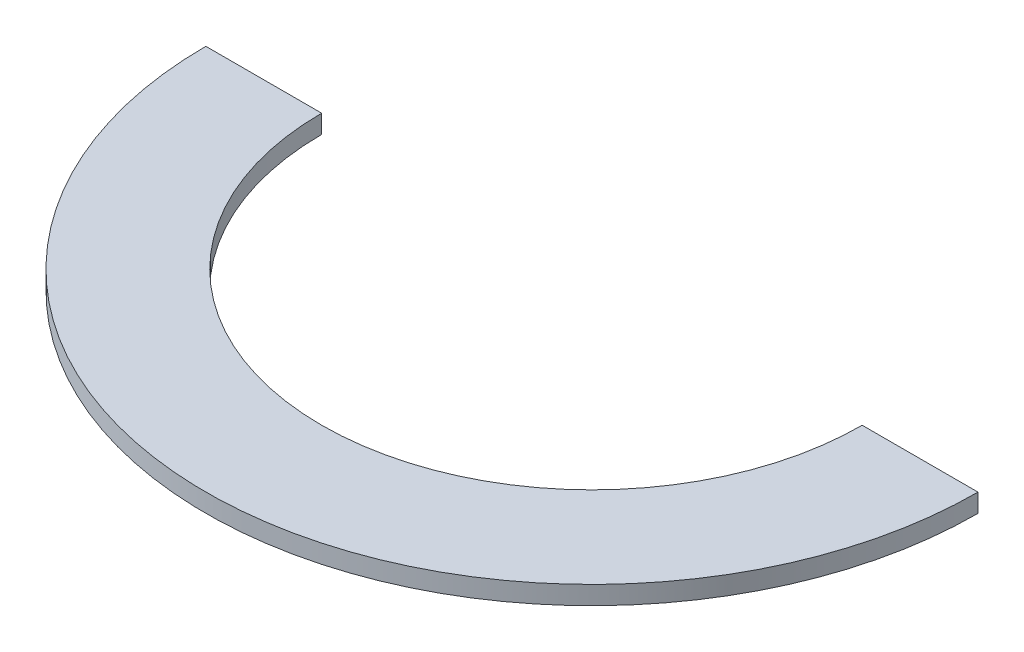
SolidWorks part; units mm, degrees
material "PETG"
ref_plane "Front Plane" through (0, 0, 0) normal (0, 0, 1) x (1, 0, 0)
ref_plane "Top Plane" through (0, 0, 0) normal (0, 1, 0) x (1, 0, 0)
ref_plane "Right Plane" through (0, 0, 0) normal (1, 0, 0) x (0, 0, -1)
sketch "Sketch1" plane through (0, 0, 0) normal (0, 1, 0) x (1, 0, 0)
  line L0 (-50, 0) -> (-35, 0)
  line L1 (35, 0) -> (50, 0)
  arc A0 (-50, 0) -> (50, 0) centre (0, 0) ccw
  arc A1 (-35, 0) -> (35, 0) centre (0, 0) ccw
  dimension "D1" = 50
  dimension "D2" = 35
extrude "Boss-Extrude1" add sketch "Sketch1" along normal blind 2.3875
equation "\"D1@Boss-Extrude1\"=1in / 16 + 0.8mm"
